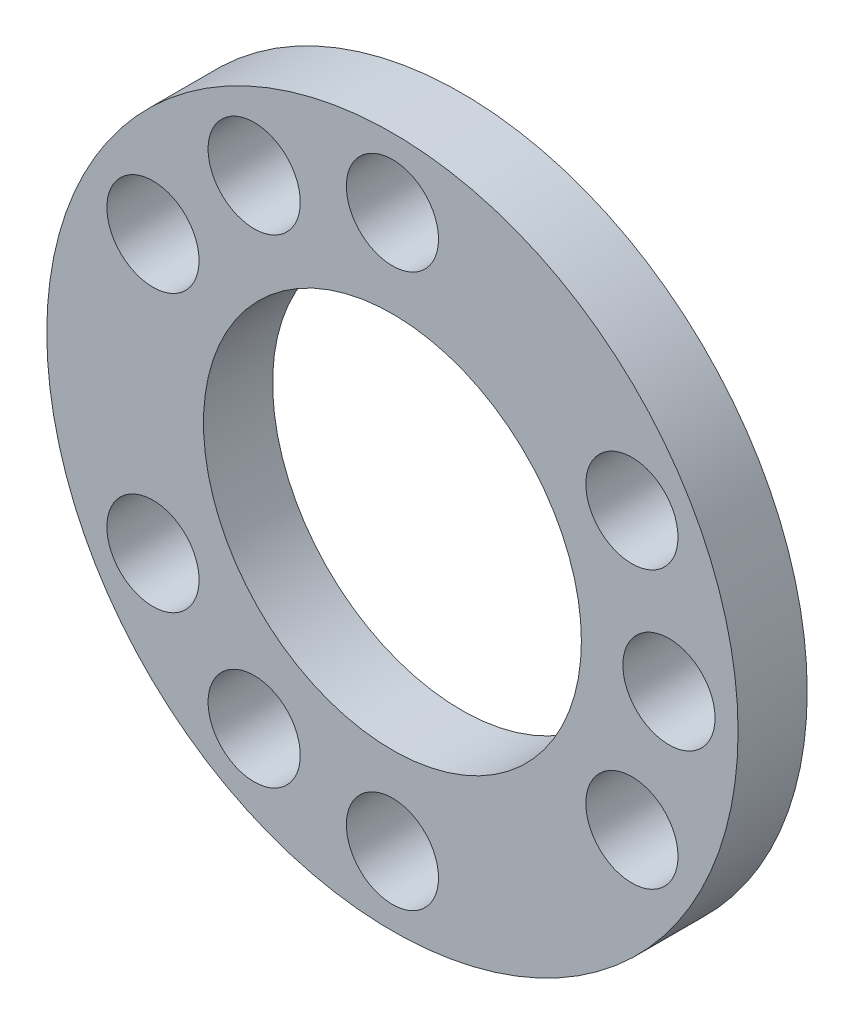
SolidWorks part; units mm, degrees
ref_plane "前视基准面" through (0, 0, 0) normal (0, 0, 1) x (1, 0, 0)
ref_plane "上视基准面" through (0, 0, 0) normal (0, 1, 0) x (1, 0, 0)
ref_plane "右视基准面" through (0, 0, 0) normal (1, 0, 0) x (0, 0, -1)
sketch "草图1" plane through (0, 0, 0) normal (0, 0, 1) x (1, 0, 0)
  circle A0 centre (0, 0) radius 15
  circle A2 centre (0, 12) radius 2
  circle A3 centre (10.3923, 6) radius 2
  circle A4 centre (10.3923, -6) radius 2
  circle A5 centre (0, -12) radius 2
  circle A6 centre (-10.3923, -6) radius 2
  circle A7 centre (-10.3923, 6) radius 2
  circle A8 centre (-6, 10.3923) radius 2
  circle A9 centre (12, 0) radius 2
  circle A10 centre (-6, -10.3923) radius 2
  circle A11 centre (0, 0) radius 5
  dimension "D1" = 30
  dimension "D2" = 6
  dimension "D4" = 3
extrude "凸台-拉伸1" add sketch "草图1" along normal blind 7
sketch "草图2" plane through (0, 0, 7) normal (0, 0, 1) x (1, 0, 0)
  circle A0 centre (0, 0) radius 8
  circle A1 centre (0, 0) radius 5
extrude "凸台-拉伸2" add sketch "草图2" along normal blind 70
sketch "草图3" plane through (0, 0, 0) normal (0, 1, 0) x (1, 0, 0)
  circle A0 centre (0.6768, -59) radius 2.5
extrude "切除-拉伸1" cut sketch "草图3" against normal blind 10
sketch "草图4" plane through (0, 0, 7) normal (0, 0, 1) x (1, 0, 0)
  circle A0 centre (0, 0) radius 8
  circle A1 centre (0, 0) radius 18.074
extrude "切除-拉伸2" cut sketch "草图4" against normal blind 4
sketch "草图5" plane through (0, 0, 77) normal (0, 0, 1) x (1, 0, 0)
  circle A0 centre (0, 0) radius 8.2
extrude "切除-拉伸3" cut sketch "草图5" against normal blind 90
